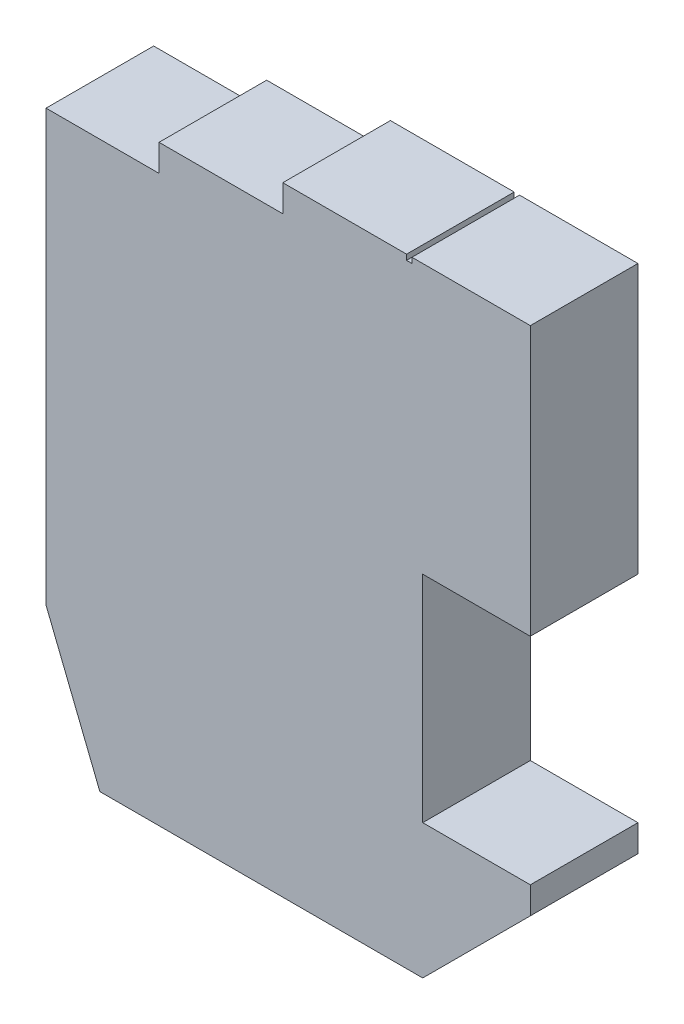
SolidWorks part; units mm, degrees
ref_plane "Front Plane" through (0, 0, 0) normal (0, 0, 1) x (1, 0, 0)
ref_plane "Top Plane" through (0, 0, 0) normal (0, 1, 0) x (1, 0, 0)
ref_plane "Right Plane" through (0, 0, 0) normal (1, 0, 0) x (0, 0, -1)
sketch "Sketch1" plane through (0, 0, 0) normal (0, 0, 1) x (1, 0, 0)
  line L0 (0, 0) -> (60, 0)
  line L1 (60, 0) -> (80, 20)
  line L2 (80, 20) -> (80, 115)
  line L3 (80, 115) -> (58, 115)
  line L4 (-10, 105) -> (11, 105)
  line L5 (-10, 105) -> (-10, 25)
  line L6 (-10, 25) -> (0, 0)
  line L7 (57, 115) -> (57, 114)
  line L8 (35, 115) -> (57, 115)
  line L9 (34, 115) -> (34, 110)
  line L10 (35, 115) -> (34, 115)
  line L11 (34, 110) -> (12, 110)
  line L12 (12, 110) -> (11, 110)
  line L13 (11, 110) -> (11, 105)
  line L14 (57, 115) -> (58, 115)
  line L15 (57, 114) -> (58, 114)
  line L16 (58, 114) -> (58, 115)
  dimension "D1" = 60
  dimension "D2" = 22
  dimension "D3" = 90
  dimension "D4" = 20
  dimension "D5" = 80
  dimension "D6" = 95
  dimension "D7" = 135
  dimension "D8" = 1
  dimension "D9" = 22
  dimension "D10" = 22
  dimension "D11" = 1
  dimension "D12" = 5
  dimension "D13" = 1
  dimension "D14" = 5
  dimension "D15" = 1
extrude "Boss-Extrude1" add sketch "Sketch1" along normal blind 20 contours L16 L15 L7 L8 L10 L9 L11 L12 L13 L4 L5 L6 L0 L1 L2 L3
sketch "Sketch2" plane through (0, 0, 20) normal (0, 0, 1) x (1, 0, 0)
  line L0 (80, 25) -> (60, 25)
  line L2 (60, 25) -> (60, 65)
  line L3 (60, 65) -> (80, 65)
  line L4 (80, 65) -> (80, 25)
  point P4 (0, 0)
  point P7 (0, 0)
  point P9 (0, 0)
  dimension "D1" = 20
  dimension "D2" = 5
  dimension "D3" = 40
extrude "Cut-Extrude1" cut sketch "Sketch2" against normal through all
